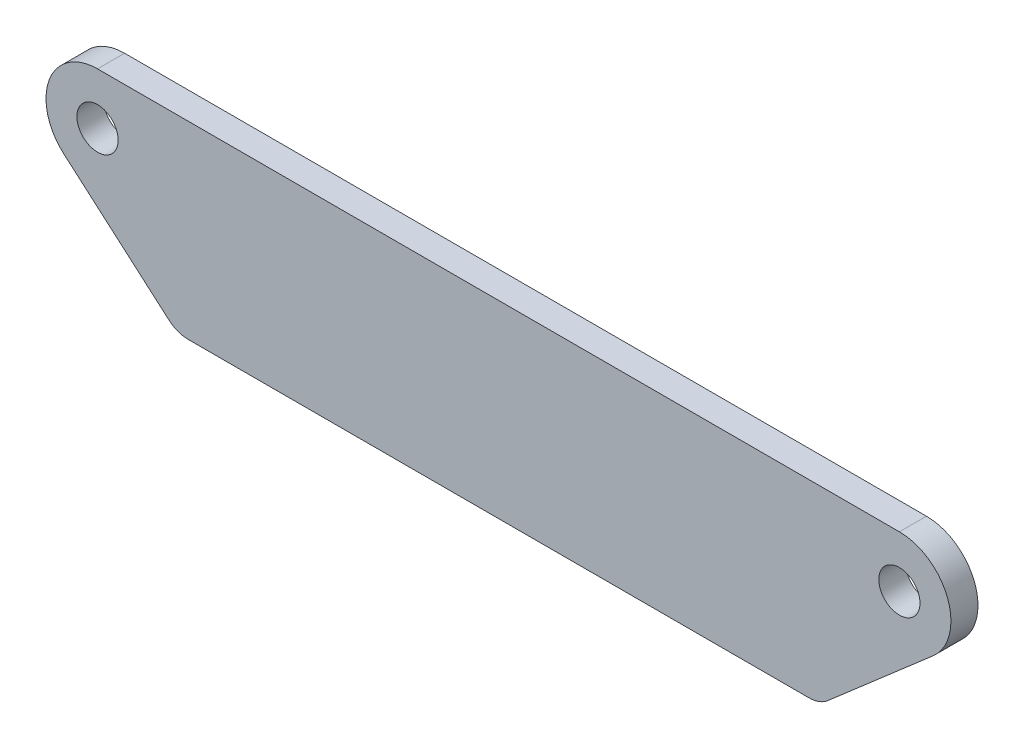
SolidWorks part; units mm, degrees
material "Custom Plastic"
ref_plane "Front Plane" through (0, 0, 0) normal (0, 0, 1) x (1, 0, 0)
ref_plane "Top Plane" through (0, 0, 0) normal (0, 1, 0) x (1, 0, 0)
ref_plane "Right Plane" through (0, 0, 0) normal (1, 0, 0) x (0, 0, -1)
sketch "Sketch1" plane through (0, 0, 0) normal (0, 0, 1) x (1, 0, 0)
  line L0 (0, 6.35) -> (0, -6.35) construction
  line L1 (0, -6.35) -> (88.9, -6.35) construction
  line L2 (88.9, -6.35) -> (0, 6.35) construction
  line L3 (0, 6.35) -> (88.9, 6.35) construction
  line L4 (88.9, 6.35) -> (88.9, -6.35) construction
  line L5 (-3.7475, 2.0352) -> (7.9361, -8.1121)
  line L6 (10.018, -8.89) -> (78.882, -8.89)
  line L8 (92.6475, 2.0352) -> (80.9639, -8.1121)
  line L9 (0, 12.065) -> (88.9, 12.065)
  circle A0 centre (0, 6.35) radius 2.286
  circle A1 centre (0, -6.35) radius 3.8735 construction
  circle A2 centre (88.9, -6.35) radius 3.8735 construction
  circle A3 centre (0, -6.35) radius 5.715 construction
  circle A4 centre (0, 6.35) radius 5.715 construction
  circle A5 centre (88.9, -6.35) radius 5.715 construction
  circle A6 centre (88.9, 6.35) radius 2.286
  circle A7 centre (88.9, 6.35) radius 5.715 construction
  arc A8 (80.9639, -8.1121) -> (78.882, -8.89) centre (78.882, -5.715) cw
  arc A9 (7.9361, -8.1121) -> (10.018, -8.89) centre (10.018, -5.715) ccw
  arc A10 (-3.7475, 2.0352) -> (0, 12.065) centre (0, 6.35) cw
  arc A11 (88.9, 12.065) -> (92.6475, 2.0352) centre (88.9, 6.35) cw
  point P20 (8.8318, -8.89)
  dimension "D1" = 7.747
  dimension "D4" = 11.43
  dimension "D5" = 3.175
  dimension "D6" = 4.572
  dimension "D2" = 12.7
  dimension "D3" = 88.9
  dimension "D7" = 8.89
extrude "Main" add sketch "Sketch1" along normal blind 3
